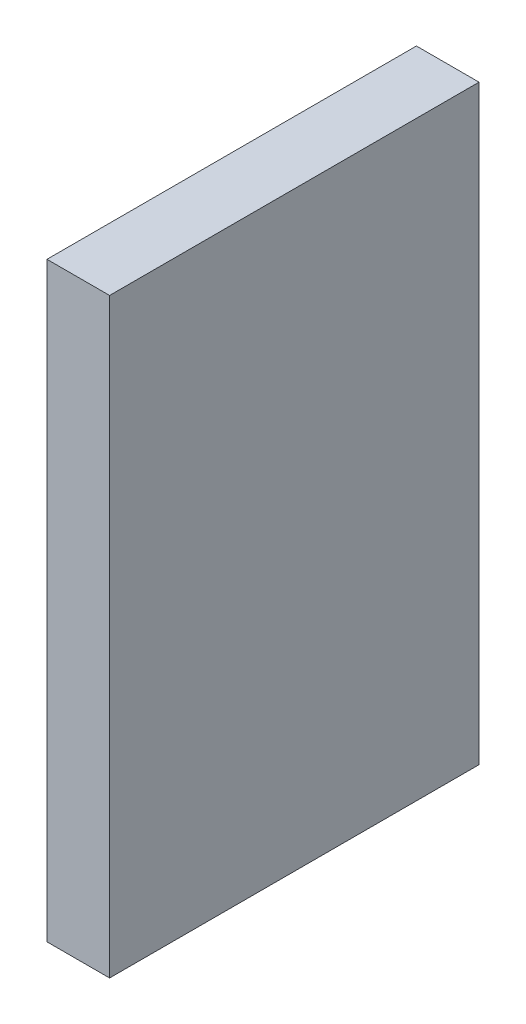
SolidWorks part; units mm, degrees
ref_plane "Front Plane" through (0, 0, 0) normal (0, 0, 1) x (1, 0, 0)
ref_plane "Top Plane" through (0, 0, 0) normal (0, 1, 0) x (1, 0, 0)
ref_plane "Right Plane" through (0, 0, 0) normal (1, 0, 0) x (0, 0, -1)
sketch "Sketch2" plane through (0, 0, 0) normal (0, 1, 0) x (1, 0, 0)
  line L1 (-31.75, 200.025) -> (31.75, 200.025)
  line L2 (-31.75, 200.025) -> (-31.75, -174.625)
  line L3 (-31.75, -174.625) -> (31.75, -174.625)
  line L4 (31.75, 200.025) -> (31.75, -174.625)
  dimension "D1" = 374.65
  dimension "D2" = 63.5
  dimension "D3" = 31.75
  dimension "D4" = 174.625
extrude "Boss-Extrude1" add sketch "Sketch2" along normal mid plane 599.44
